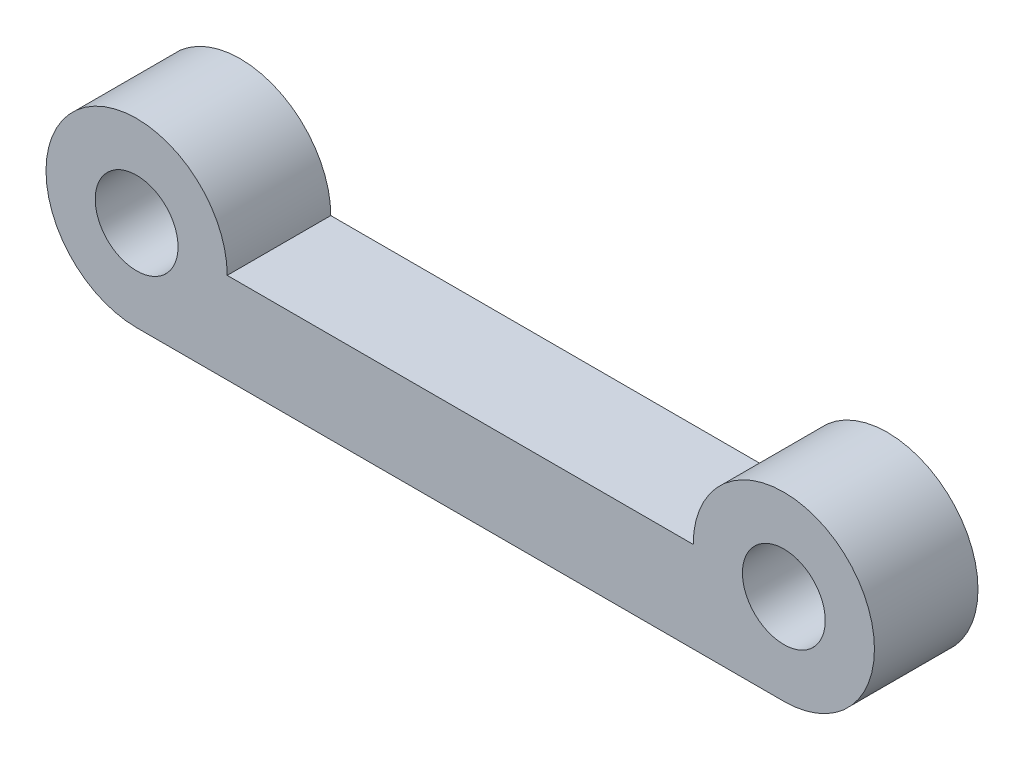
SolidWorks part; units mm, degrees
ref_plane "正面" through (0, 0, 0) normal (0, 0, 1) x (1, 0, 0)
ref_plane "平面" through (0, 0, 0) normal (0, 1, 0) x (1, 0, 0)
ref_plane "右側面" through (0, 0, 0) normal (1, 0, 0) x (0, 0, -1)
sketch "ｽｹｯﾁ1" plane through (0, 0, 0) normal (0, 0, 1) x (1, 0, 0)
  line L0 (0, -3.5) -> (25, -3.5)
  line L1 (3.5, 0) -> (21.5, 0)
  arc A0 (3.5, 0) -> (0, -3.5) centre (0, 0) ccw
  arc A1 (25, -3.5) -> (21.5, 0) centre (25, 0) ccw
  circle A2 centre (0, 0) radius 1.6
  circle A3 centre (25, 0) radius 1.6
  dimension "D3" = 7
  dimension "D4" = 7
  dimension "D2" = 3.2
  dimension "D5" = 3.2
  dimension "D1" = 25
extrude "ﾎﾞｽ - 押し出し1" add sketch "ｽｹｯﾁ1" along normal blind 4
